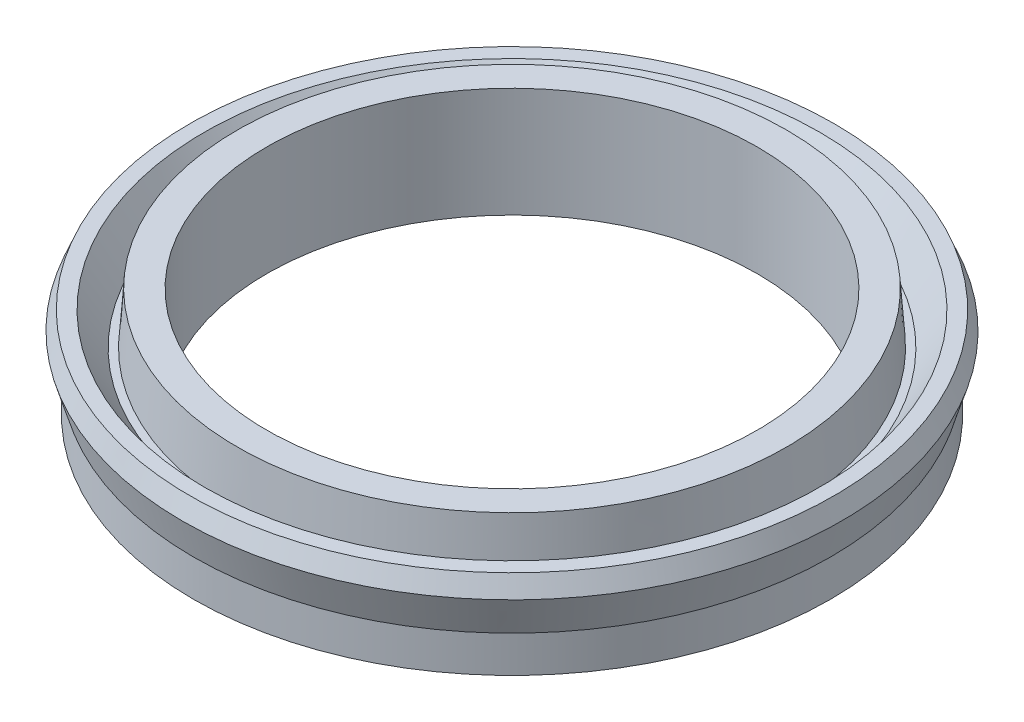
SolidWorks part; units mm, degrees
material "Silicon Rubber"
ref_plane "Front Plane" through (0, 0, 0) normal (0, 0, 1) x (1, 0, 0)
ref_plane "Top Plane" through (0, 0, 0) normal (0, 1, 0) x (1, 0, 0)
ref_plane "Right Plane" through (0, 0, 0) normal (1, 0, 0) x (0, 0, -1)
sketch "SealProfileS" plane through (0, 0, 0) normal (0, 0, 1) x (1, 0, 0)
  line L0 (6.7, 0) -> (6.7, 3)
  line L1 (6.7, 3) -> (7.5, 3)
  line L2 (7.5, 3) -> (7.6, 1.6)
  line L3 (7.6, 1.6) -> (7.8, 1.6)
  line L4 (7.8, 1.6) -> (8.4, 2.5)
  line L5 (8.4, 2.5) -> (8.8, 2.5)
  line L6 (8.8, 2.5) -> (9, 2)
  line L7 (9, 2) -> (8.7, 1)
  line L8 (8.7, 1) -> (8.7, 0)
  line L9 (8.7, 0) -> (6.7, 0)
  line L10 (0, 0) -> (0, 3) construction
  line L11 (0, 0) -> (6.7, 0) construction
  point P13 (9.4532, 2.3857)
  point P14 (8.5578, 2.7686)
  point P15 (7.884, 1.0263)
  point P16 (8.345, 2.5)
  point P17 (8.8739, 2.5)
  point P18 (8.5815, 2.5)
  point P19 (7.8762, 1.015)
  point P20 (0, 0)
  point P21 (7.5925, 0.9436)
  dimension "ID" = 13.4
  dimension "Thickness" = 2
  dimension "Height" = 3
  dimension "HeightDiffOutsideWall" = 0.5
  dimension "OuterChamferHeight" = 0.5
  dimension "BaseOuterHeight" = 1
  dimension "InnerThickness" = 0.8
  dimension "OuterThickness" = 0.4
  dimension "OuterChamferWidth" = 0.3
  dimension "RefDia" = 18
  dimension "InnerGrooveWidth" = 0.2
  dimension "GrooveDraftLeft" = 0.1
  dimension "GrooveDraftRight" = 0.6
  dimension "InnerGrooveHeight" = 1.4
revolve "SealProfile" add sketch "SealProfileS" angle 360 about L10
